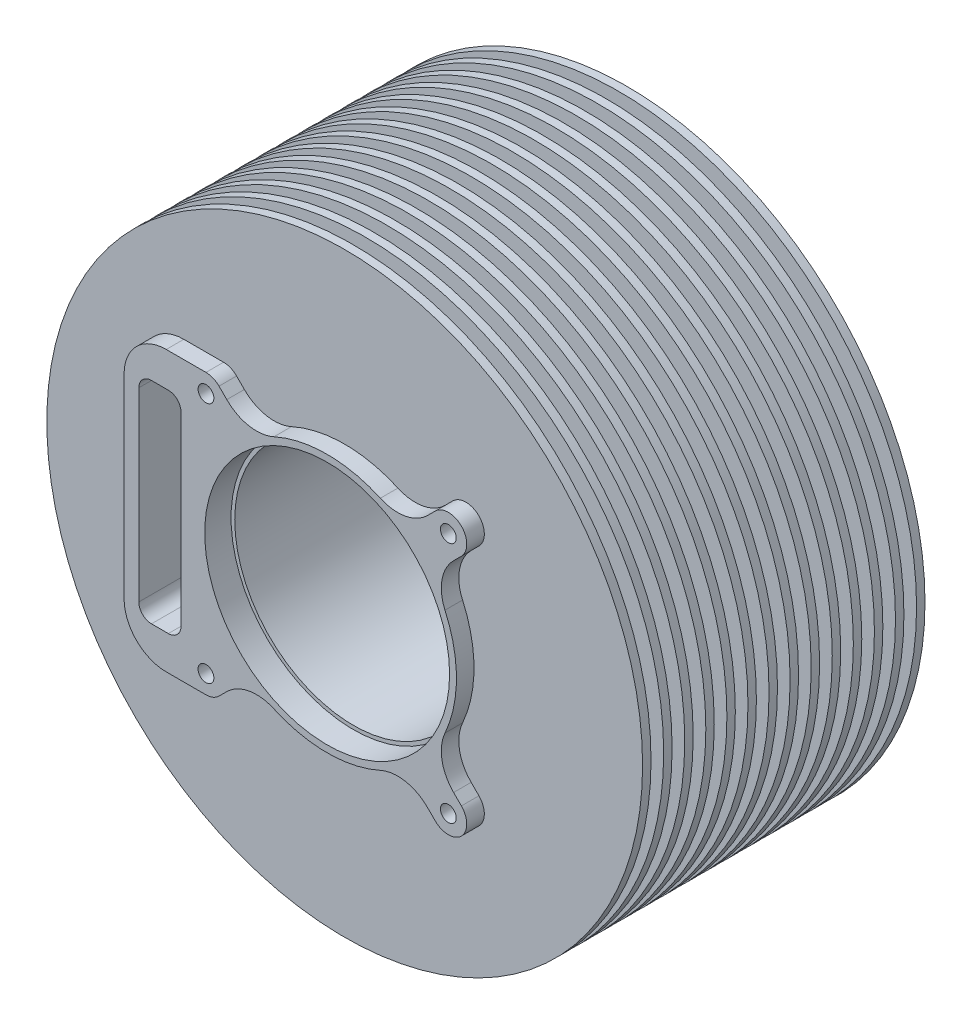
SolidWorks part; units mm, degrees
material "2024-T3"
ref_plane "Front Plane" through (0, 0, 0) normal (0, 0, 1) x (1, 0, 0)
ref_plane "Top Plane" through (0, 0, 0) normal (0, 1, 0) x (1, 0, 0)
ref_plane "Right Plane" through (0, 0, 0) normal (1, 0, 0) x (0, 0, -1)
sketch "Sketch1" plane through (0, 0, 0) normal (0, 0, 1) x (1, 0, 0)
  line L8 (-91.7539, 59.9982) -> (-95.4428, 63.6872)
  line L9 (-107.8172, 51.3128) -> (-104.1282, 47.6239)
  line L10 (-104.1282, -47.6239) -> (-107.8172, -51.3128)
  line L11 (-95.4428, -63.6872) -> (-91.7539, -59.9982)
  line L12 (3.4939, -59.9982) -> (7.1828, -63.6872)
  line L13 (19.5572, -51.3128) -> (15.8682, -47.6239)
  line L14 (15.8682, 47.6239) -> (19.5572, 51.3128)
  line L15 (7.1828, 63.6872) -> (3.4939, 59.9982)
  line L16 (-91.7539, 59.9982) -> (-95.4428, 63.6872)
  line L17 (-107.8172, 51.3128) -> (-104.1282, 47.6239)
  line L18 (-104.1282, -47.6239) -> (-107.8172, -51.3128)
  line L19 (-95.4428, -63.6872) -> (-91.7539, -59.9982)
  line L20 (3.4939, -59.9982) -> (7.1828, -63.6872)
  line L21 (19.5572, -51.3128) -> (15.8682, -47.6239)
  line L22 (15.8682, 47.6239) -> (19.5572, 51.3128)
  line L23 (7.1828, 63.6872) -> (3.4939, 59.9982)
  circle A0 centre (-101.63, -57.5) radius 3.75 construction
  circle A1 centre (13.37, -57.5) radius 3.75 construction
  circle A2 centre (13.37, 57.5) radius 3.75 construction
  circle A3 centre (-44.13, 0) radius 56.35 construction
  circle A4 centre (-101.63, 57.5) radius 3.75 construction
  circle A5 centre (-101.63, -57.5) radius 3.75
  circle A6 centre (13.37, -57.5) radius 3.75
  circle A7 centre (13.37, 57.5) radius 3.75
  circle A8 centre (-44.13, 0) radius 56.35
  circle A9 centre (-101.63, 57.5) radius 3.75
  arc A16 (-91.7539, 59.9982) -> (-69.3802, 55.9129) centre (-77.6117, 74.1404) ccw
  arc A17 (-95.4428, 63.6872) -> (-107.8172, 51.3128) centre (-101.63, 57.5) ccw
  arc A18 (-100.0429, 25.2502) -> (-104.1282, 47.6239) centre (-118.2704, 33.4817) ccw
  arc A19 (-100.0429, 25.2502) -> (-100.0429, -25.2502) centre (-44.13, 0) ccw
  arc A20 (-104.1282, -47.6239) -> (-100.0429, -25.2502) centre (-118.2704, -33.4817) ccw
  arc A21 (-107.8172, -51.3128) -> (-95.4428, -63.6872) centre (-101.63, -57.5) ccw
  arc A22 (-69.3802, -55.9129) -> (-91.7539, -59.9982) centre (-77.6117, -74.1404) ccw
  arc A23 (-69.3802, -55.9129) -> (-18.8798, -55.9129) centre (-44.13, 0) ccw
  arc A24 (3.4939, -59.9982) -> (-18.8798, -55.9129) centre (-10.6483, -74.1404) ccw
  arc A25 (7.1828, -63.6872) -> (19.5572, -51.3128) centre (13.37, -57.5) ccw
  arc A26 (11.7829, -25.2502) -> (15.8682, -47.6239) centre (30.0104, -33.4817) ccw
  arc A27 (11.7829, -25.2502) -> (11.7829, 25.2502) centre (-44.13, 0) ccw
  arc A28 (15.8682, 47.6239) -> (11.7829, 25.2502) centre (30.0104, 33.4817) ccw
  arc A29 (19.5572, 51.3128) -> (7.1828, 63.6872) centre (13.37, 57.5) ccw
  arc A30 (-18.8798, 55.9129) -> (3.4939, 59.9982) centre (-10.6483, 74.1404) ccw
  arc A31 (-18.8798, 55.9129) -> (-69.3802, 55.9129) centre (-44.13, 0) ccw
  arc A32 (-91.7539, 59.9982) -> (-69.3802, 55.9129) centre (-77.6117, 74.1404) ccw
  arc A33 (-95.4428, 63.6872) -> (-107.8172, 51.3128) centre (-101.63, 57.5) ccw
  arc A34 (-100.0429, 25.2502) -> (-104.1282, 47.6239) centre (-118.2704, 33.4817) ccw
  arc A35 (-100.0429, 25.2502) -> (-100.0429, -25.2502) centre (-44.13, 0) ccw
  arc A36 (-104.1282, -47.6239) -> (-100.0429, -25.2502) centre (-118.2704, -33.4817) ccw
  arc A37 (-107.8172, -51.3128) -> (-95.4428, -63.6872) centre (-101.63, -57.5) ccw
  arc A38 (-69.3802, -55.9129) -> (-91.7539, -59.9982) centre (-77.6117, -74.1404) ccw
  arc A39 (-69.3802, -55.9129) -> (-18.8798, -55.9129) centre (-44.13, 0) ccw
  arc A40 (3.4939, -59.9982) -> (-18.8798, -55.9129) centre (-10.6483, -74.1404) ccw
  arc A41 (7.1828, -63.6872) -> (19.5572, -51.3128) centre (13.37, -57.5) ccw
  arc A42 (11.7829, -25.2502) -> (15.8682, -47.6239) centre (30.0104, -33.4817) ccw
  arc A43 (11.7829, -25.2502) -> (11.7829, 25.2502) centre (-44.13, 0) ccw
  arc A44 (15.8682, 47.6239) -> (11.7829, 25.2502) centre (30.0104, 33.4817) ccw
  arc A45 (19.5572, 51.3128) -> (7.1828, 63.6872) centre (13.37, 57.5) ccw
  arc A46 (-18.8798, 55.9129) -> (3.4939, 59.9982) centre (-10.6483, 74.1404) ccw
  arc A47 (-18.8798, 55.9129) -> (-69.3802, 55.9129) centre (-44.13, 0) ccw
  dimension "D1" = 0
extrude "Boss-Extrude1" add sketch "Sketch1" along normal blind 142.33
sketch "Sketch2" plane through (0, 0, 142.33) normal (0, 0, 1) x (1, 0, 0)
  circle A0 centre (-44.13, 0) radius 58.1
  dimension "D1" = 116.2
extrude "Cut-Extrude1" cut sketch "Sketch2" against normal blind 12.5
sketch "Sketch4" plane through (0, 0, 0) normal (0, 0, 1) x (1, 0, 0)
  line L0 (-104.1282, -47.6239) -> (-107.8172, -51.3128) construction
  line L1 (-107.8172, 51.3128) -> (-104.1282, 47.6239) construction
  line L2 (-104.1282, -47.6239) -> (-107.8172, -51.3128)
  line L3 (-107.8172, 51.3128) -> (-104.1282, 47.6239)
  line L4 (-101.63, 66.25) -> (-120.48, 66.25)
  line L5 (-140.48, 46.25) -> (-140.48, -46.25)
  line L6 (-120.48, -66.25) -> (-101.63, -66.25)
  line L8 (-127.48, 50) -> (-119.48, 50)
  line L9 (-133.48, 44) -> (-133.48, -44)
  line L10 (-127.48, -50) -> (-119.48, -50)
  line L11 (-113.48, 44) -> (-113.48, -44)
  arc A0 (-107.8172, -51.3128) -> (-95.4428, -63.6872) centre (-101.63, -57.5) ccw construction
  arc A1 (-104.1282, -47.6239) -> (-100.0429, -25.2502) centre (-118.2704, -33.4817) ccw construction
  arc A2 (-100.0429, 25.2502) -> (-100.0429, -25.2502) centre (-44.13, 0) ccw construction
  arc A3 (-95.4428, 63.6872) -> (-107.8172, 51.3128) centre (-101.63, 57.5) ccw construction
  arc A4 (-100.0429, 25.2502) -> (-104.1282, 47.6239) centre (-118.2704, 33.4817) ccw construction
  arc A5 (-107.8172, -51.3128) -> (-101.63, -66.25) centre (-101.63, -57.5) ccw
  arc A6 (-104.1282, -47.6239) -> (-100.0429, -25.2502) centre (-118.2704, -33.4817) ccw
  arc A7 (-100.0429, 25.2502) -> (-100.0429, -25.2502) centre (-44.13, 0) ccw
  arc A8 (-101.63, 66.25) -> (-107.8172, 51.3128) centre (-101.63, 57.5) ccw
  arc A9 (-100.0429, 25.2502) -> (-104.1282, 47.6239) centre (-118.2704, 33.4817) ccw
  arc A10 (-119.48, -50) -> (-113.48, -44) centre (-119.48, -44) ccw
  arc A11 (-133.48, -44) -> (-127.48, -50) centre (-127.48, -44) ccw
  arc A12 (-119.48, 50) -> (-113.48, 44) centre (-119.48, 44) cw
  arc A13 (-127.48, 50) -> (-133.48, 44) centre (-127.48, 44) ccw
  arc A14 (-140.48, -46.25) -> (-120.48, -66.25) centre (-120.48, -46.25) ccw
  arc A15 (-120.48, 66.25) -> (-140.48, 46.25) centre (-120.48, 46.25) ccw
  point P27 (-113.48, 50)
  point P30 (-133.48, 50)
  point P35 (-133.48, 0)
  point P36 (-140.48, 0)
  point P37 (-105.48, 0)
  dimension "D3" = 6
  dimension "D4" = 20
  dimension "D1" = 100
  dimension "D2" = 20
  dimension "D5" = 35
  dimension "D6" = 7
extrude "Boss-Extrude2" add sketch "Sketch4" along normal blind 142.33
sketch "Sketch5" plane through (0, 0, 0) normal (0, 0, 1) x (1, 0, 0)
  line L0 (-101.63, 66.25) -> (-120.48, 66.25) construction
  line L1 (-91.7539, 59.9982) -> (-95.4428, 63.6872) construction
  line L2 (7.1828, 63.6872) -> (3.4939, 59.9982) construction
  line L3 (15.8682, 47.6239) -> (19.5572, 51.3128) construction
  line L4 (19.5572, -51.3128) -> (15.8682, -47.6239) construction
  line L5 (3.4939, -59.9982) -> (7.1828, -63.6872) construction
  line L6 (-95.4428, -63.6872) -> (-91.7539, -59.9982) construction
  line L7 (-120.48, -66.25) -> (-101.63, -66.25) construction
  line L8 (-140.48, 46.25) -> (-140.48, -46.25) construction
  line L9 (-101.63, 66.25) -> (-120.48, 66.25)
  line L10 (-91.7539, 59.9982) -> (-95.4428, 63.6872)
  line L11 (7.1828, 63.6872) -> (3.4939, 59.9982)
  line L12 (15.8682, 47.6239) -> (19.5572, 51.3128)
  line L13 (19.5572, -51.3128) -> (15.8682, -47.6239)
  line L14 (3.4939, -59.9982) -> (7.1828, -63.6872)
  line L15 (-95.4428, -63.6872) -> (-91.7539, -59.9982)
  line L16 (-120.48, -66.25) -> (-101.63, -66.25)
  line L17 (-140.48, 46.25) -> (-140.48, -46.25)
  line L18 (-127.48, -50) -> (-119.48, -50) construction
  line L19 (-133.48, 44) -> (-133.48, -44) construction
  line L20 (-119.48, 50) -> (-127.48, 50) construction
  line L21 (-113.48, -44) -> (-113.48, 44) construction
  line L22 (-127.48, -50) -> (-119.48, -50)
  line L23 (-133.48, 44) -> (-133.48, -44)
  line L24 (-119.48, 50) -> (-127.48, 50)
  line L25 (-113.48, -44) -> (-113.48, 44)
  arc A0 (-95.4428, 63.6872) -> (-101.63, 66.25) centre (-101.63, 57.5) ccw construction
  arc A1 (-91.7539, 59.9982) -> (-69.3802, 55.9129) centre (-77.6117, 74.1404) ccw construction
  arc A2 (-18.8798, 55.9129) -> (-69.3802, 55.9129) centre (-44.13, 0) ccw construction
  arc A3 (-18.8798, 55.9129) -> (3.4939, 59.9982) centre (-10.6483, 74.1404) ccw construction
  arc A4 (19.5572, 51.3128) -> (7.1828, 63.6872) centre (13.37, 57.5) ccw construction
  arc A5 (15.8682, 47.6239) -> (11.7829, 25.2502) centre (30.0104, 33.4817) ccw construction
  arc A6 (11.7829, -25.2502) -> (11.7829, 25.2502) centre (-44.13, 0) ccw construction
  arc A7 (11.7829, -25.2502) -> (15.8682, -47.6239) centre (30.0104, -33.4817) ccw construction
  arc A8 (7.1828, -63.6872) -> (19.5572, -51.3128) centre (13.37, -57.5) ccw construction
  arc A9 (3.4939, -59.9982) -> (-18.8798, -55.9129) centre (-10.6483, -74.1404) ccw construction
  arc A10 (-69.3802, -55.9129) -> (-18.8798, -55.9129) centre (-44.13, 0) ccw construction
  arc A11 (-69.3802, -55.9129) -> (-91.7539, -59.9982) centre (-77.6117, -74.1404) ccw construction
  arc A12 (-101.63, -66.25) -> (-95.4428, -63.6872) centre (-101.63, -57.5) ccw construction
  arc A13 (-140.48, -46.25) -> (-120.48, -66.25) centre (-120.48, -46.25) ccw construction
  arc A14 (-120.48, 66.25) -> (-140.48, 46.25) centre (-120.48, 46.25) ccw construction
  arc A15 (-95.4428, 63.6872) -> (-101.63, 66.25) centre (-101.63, 57.5) ccw
  arc A16 (-91.7539, 59.9982) -> (-69.3802, 55.9129) centre (-77.6117, 74.1404) ccw
  arc A17 (-18.8798, 55.9129) -> (-69.3802, 55.9129) centre (-44.13, 0) ccw
  arc A18 (-18.8798, 55.9129) -> (3.4939, 59.9982) centre (-10.6483, 74.1404) ccw
  arc A19 (19.5572, 51.3128) -> (7.1828, 63.6872) centre (13.37, 57.5) ccw
  arc A20 (15.8682, 47.6239) -> (11.7829, 25.2502) centre (30.0104, 33.4817) ccw
  arc A21 (11.7829, -25.2502) -> (11.7829, 25.2502) centre (-44.13, 0) ccw
  arc A22 (11.7829, -25.2502) -> (15.8682, -47.6239) centre (30.0104, -33.4817) ccw
  arc A23 (7.1828, -63.6872) -> (19.5572, -51.3128) centre (13.37, -57.5) ccw
  arc A24 (3.4939, -59.9982) -> (-18.8798, -55.9129) centre (-10.6483, -74.1404) ccw
  arc A25 (-69.3802, -55.9129) -> (-18.8798, -55.9129) centre (-44.13, 0) ccw
  arc A26 (-69.3802, -55.9129) -> (-91.7539, -59.9982) centre (-77.6117, -74.1404) ccw
  arc A27 (-101.63, -66.25) -> (-95.4428, -63.6872) centre (-101.63, -57.5) ccw
  arc A28 (-140.48, -46.25) -> (-120.48, -66.25) centre (-120.48, -46.25) ccw
  arc A29 (-120.48, 66.25) -> (-140.48, 46.25) centre (-120.48, 46.25) ccw
  arc A30 (-119.48, -50) -> (-113.48, -44) centre (-119.48, -44) ccw construction
  arc A31 (-133.48, -44) -> (-127.48, -50) centre (-127.48, -44) ccw construction
  arc A32 (-127.48, 50) -> (-133.48, 44) centre (-127.48, 44) ccw construction
  arc A33 (-113.48, 44) -> (-119.48, 50) centre (-119.48, 44) ccw construction
  circle A34 centre (13.37, -57.5) radius 3.75 construction
  circle A35 centre (-101.63, -57.5) radius 3.75 construction
  circle A36 centre (13.37, 57.5) radius 3.75 construction
  circle A37 centre (-101.63, 57.5) radius 3.75 construction
  arc A38 (-119.48, -50) -> (-113.48, -44) centre (-119.48, -44) ccw
  arc A39 (-133.48, -44) -> (-127.48, -50) centre (-127.48, -44) ccw
  arc A40 (-127.48, 50) -> (-133.48, 44) centre (-127.48, 44) ccw
  arc A41 (-113.48, 44) -> (-119.48, 50) centre (-119.48, 44) ccw
  circle A42 centre (13.37, -57.5) radius 3.75
  circle A43 centre (-101.63, -57.5) radius 3.75
  circle A44 centre (13.37, 57.5) radius 3.75
  circle A45 centre (-101.63, 57.5) radius 3.75
  circle A46 centre (-44.13, 0) radius 56.35 construction
  circle A47 centre (-44.13, 0) radius 56.35
  circle A48 centre (-44.13, 0) radius 141.35
  dimension "D1" = 80
extrude "Boss-Extrude3" add sketch "Sketch5" along normal blind 4 contours A48 A29 L9 A15 L10 A16 A17 A18 L11 A19 L12 A20 A21 A22 L13 A23 L14 A24 A25 A26 L15 A27 L16 A28 L17
pattern_linear "LPattern1" count 14 spacing 10 along (0, 0, 1) of "Boss-Extrude3"
sketch "Sketch3" plane through (0, 0, 0) normal (0, 0, 1) x (1, 0, 0)
  circle A0 centre (-44.13, 0) radius 171.35
  arc A1 (-18.8798, 55.9129) -> (-69.3802, 55.9129) centre (-44.13, 0) ccw construction
  circle A2 centre (-44.13, 0) radius 56.35 construction
  circle A3 centre (-101.63, -57.5) radius 3.75 construction
  circle A4 centre (13.37, -57.5) radius 3.75 construction
  circle A5 centre (13.37, 57.5) radius 3.75 construction
  circle A6 centre (-101.63, 57.5) radius 3.75 construction
  circle A7 centre (-44.13, 0) radius 56.35
  circle A8 centre (-101.63, -57.5) radius 3.75
  circle A9 centre (13.37, -57.5) radius 3.75
  circle A10 centre (13.37, 57.5) radius 3.75
  circle A11 centre (-101.63, 57.5) radius 3.75
  dimension "D1" = 110
equation "\"Cylinder Length\"= 169.33"
equation "\"Liner Offset\"= 27"
equation "\"D1@Boss-Extrude1\"=\"Cylinder Length\"-\"Liner Offset\""
equation "\"D1@Sketch2\"=118.2-2"
equation "\"f\"= 118.2 + 2"
